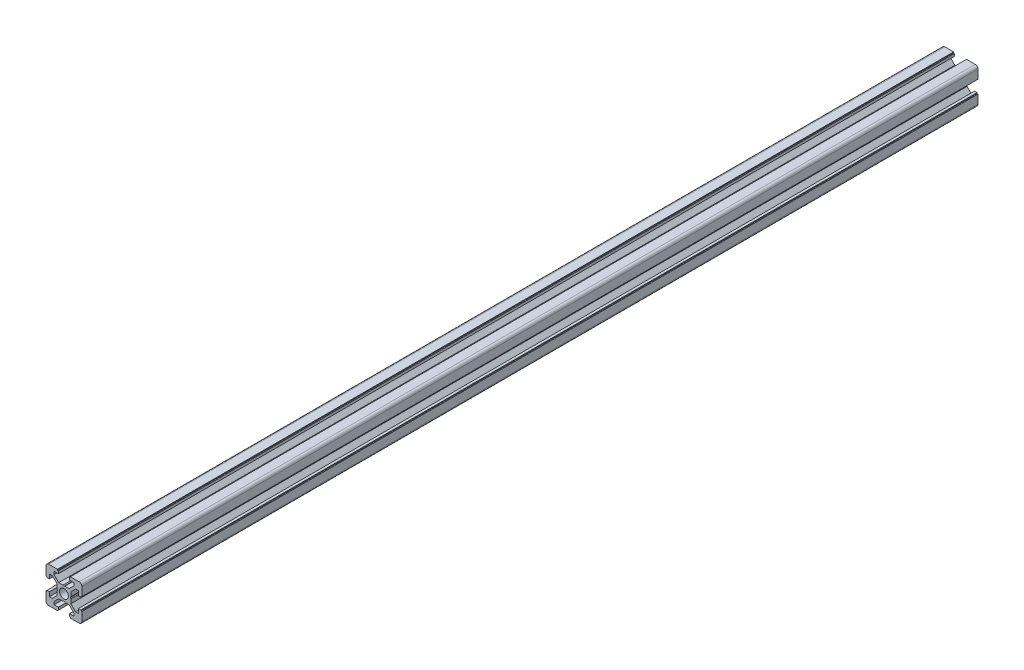
SolidWorks part; units mm, degrees
ref_plane "前视基准面" through (0, 0, 0) normal (0, 0, 1) x (1, 0, 0)
ref_plane "上视基准面" through (0, 0, 0) normal (0, 1, 0) x (1, 0, 0)
ref_plane "右视基准面" through (0, 0, 0) normal (1, 0, 0) x (0, 0, -1)
sketch "Model" plane through (0, 0, 0) normal (0, 0, 1) x (1, 0, 0)
  line L0 (-3.9, 0.5196) -> (-3.6, 0)
  line L1 (-3.6, 0) -> (-3.9, -0.5196)
  line L2 (-3.9, -0.5196) -> (-3.9, -2.9101)
  line L3 (-3.9, -2.9101) -> (-6.4899, -5.5)
  line L4 (-6.4899, -5.5) -> (-8.1, -5.5)
  line L5 (-8.1, -5.5) -> (-8.1, -3.1)
  line L6 (-8.1, -3.1) -> (-9.5, -3.1)
  line L7 (-9.5, -3.1) -> (-9.5, -3.6)
  line L8 (-9.5, -3.6) -> (-10, -3.6)
  line L9 (-10, -3.6) -> (-10, -8.5)
  line L10 (-8.5, -10) -> (-3.6, -10)
  line L11 (-3.6, -10) -> (-3.6, -9.5)
  line L12 (-3.6, -9.5) -> (-3.1, -9.5)
  line L13 (-3.1, -9.5) -> (-3.1, -8.1)
  line L14 (-3.1, -8.1) -> (-5.5, -8.1)
  line L15 (-5.5, -8.1) -> (-5.5, -6.4899)
  line L16 (-5.5, -6.4899) -> (-2.9101, -3.9)
  line L17 (-2.9101, -3.9) -> (-0.5196, -3.9)
  line L18 (-0.5196, -3.9) -> (0, -3.6)
  line L19 (0, -3.6) -> (0.5196, -3.9)
  line L20 (0.5196, -3.9) -> (2.9101, -3.9)
  line L21 (2.9101, -3.9) -> (5.5, -6.4899)
  line L22 (5.5, -6.4899) -> (5.5, -8.1)
  line L23 (5.5, -8.1) -> (3.1, -8.1)
  line L24 (3.1, -8.1) -> (3.1, -9.5)
  line L25 (3.1, -9.5) -> (3.6, -9.5)
  line L26 (3.6, -9.5) -> (3.6, -10)
  line L27 (3.6, -10) -> (8.5, -10)
  line L28 (10, -8.5) -> (10, -3.6)
  line L29 (10, -3.6) -> (9.5, -3.6)
  line L30 (9.5, -3.6) -> (9.5, -3.1)
  line L31 (9.5, -3.1) -> (8.1, -3.1)
  line L32 (8.1, -3.1) -> (8.1, -5.5)
  line L33 (8.1, -5.5) -> (6.4899, -5.5)
  line L34 (6.4899, -5.5) -> (3.9, -2.9101)
  line L35 (3.9, -2.9101) -> (3.9, -0.5196)
  line L36 (3.9, -0.5196) -> (3.6, 0)
  line L37 (3.6, 0) -> (3.9, 0.5196)
  line L38 (3.9, 0.5196) -> (3.9, 2.9101)
  line L39 (3.9, 2.9101) -> (6.4899, 5.5)
  line L40 (6.4899, 5.5) -> (8.1, 5.5)
  line L41 (8.1, 5.5) -> (8.1, 3.1)
  line L42 (8.1, 3.1) -> (9.5, 3.1)
  line L43 (9.5, 3.1) -> (9.5, 3.6)
  line L44 (9.5, 3.6) -> (10, 3.6)
  line L45 (10, 3.6) -> (10, 8.5)
  line L46 (8.5, 10) -> (3.6, 10)
  line L47 (3.6, 10) -> (3.6, 9.5)
  line L48 (3.6, 9.5) -> (3.1, 9.5)
  line L49 (3.1, 9.5) -> (3.1, 8.1)
  line L50 (3.1, 8.1) -> (5.5, 8.1)
  line L51 (5.5, 8.1) -> (5.5, 6.4899)
  line L52 (5.5, 6.4899) -> (2.9101, 3.9)
  line L53 (2.9101, 3.9) -> (0.5196, 3.9)
  line L54 (0.5196, 3.9) -> (0, 3.6)
  line L55 (0, 3.6) -> (-0.5196, 3.9)
  line L56 (-0.5196, 3.9) -> (-2.9101, 3.9)
  line L57 (-2.9101, 3.9) -> (-5.5, 6.4899)
  line L58 (-5.5, 6.4899) -> (-5.5, 8.1)
  line L59 (-5.5, 8.1) -> (-3.1, 8.1)
  line L60 (-3.1, 8.1) -> (-3.1, 9.5)
  line L61 (-3.1, 9.5) -> (-3.6, 9.5)
  line L62 (-3.6, 9.5) -> (-3.6, 10)
  line L63 (-3.6, 10) -> (-8.5, 10)
  line L64 (-10, 8.5) -> (-10, 3.6)
  line L65 (-10, 3.6) -> (-9.5, 3.6)
  line L66 (-9.5, 3.6) -> (-9.5, 3.1)
  line L67 (-9.5, 3.1) -> (-8.1, 3.1)
  line L68 (-8.1, 3.1) -> (-8.1, 5.5)
  line L69 (-8.1, 5.5) -> (-6.4899, 5.5)
  line L70 (-6.4899, 5.5) -> (-3.9, 2.9101)
  line L71 (-3.9, 2.9101) -> (-3.9, 0.5196)
  circle A0 centre (0, 0) radius 2.5
  arc A1 (-10, -8.5) -> (-8.5, -10) centre (-8.5, -8.5) ccw
  arc A2 (8.5, -10) -> (10, -8.5) centre (8.5, -8.5) ccw
  arc A3 (10, 8.5) -> (8.5, 10) centre (8.5, 8.5) ccw
  arc A4 (-8.5, 10) -> (-10, 8.5) centre (-8.5, 8.5) ccw
extrude "凸台-拉伸1" add sketch "Model" along normal blind 500
cosmetic thread "装饰螺纹线1"
cosmetic thread "装饰螺纹线2"
equation "\"width\"= 500"
equation "\"D1@凸台-拉伸1\"=\"width\""
